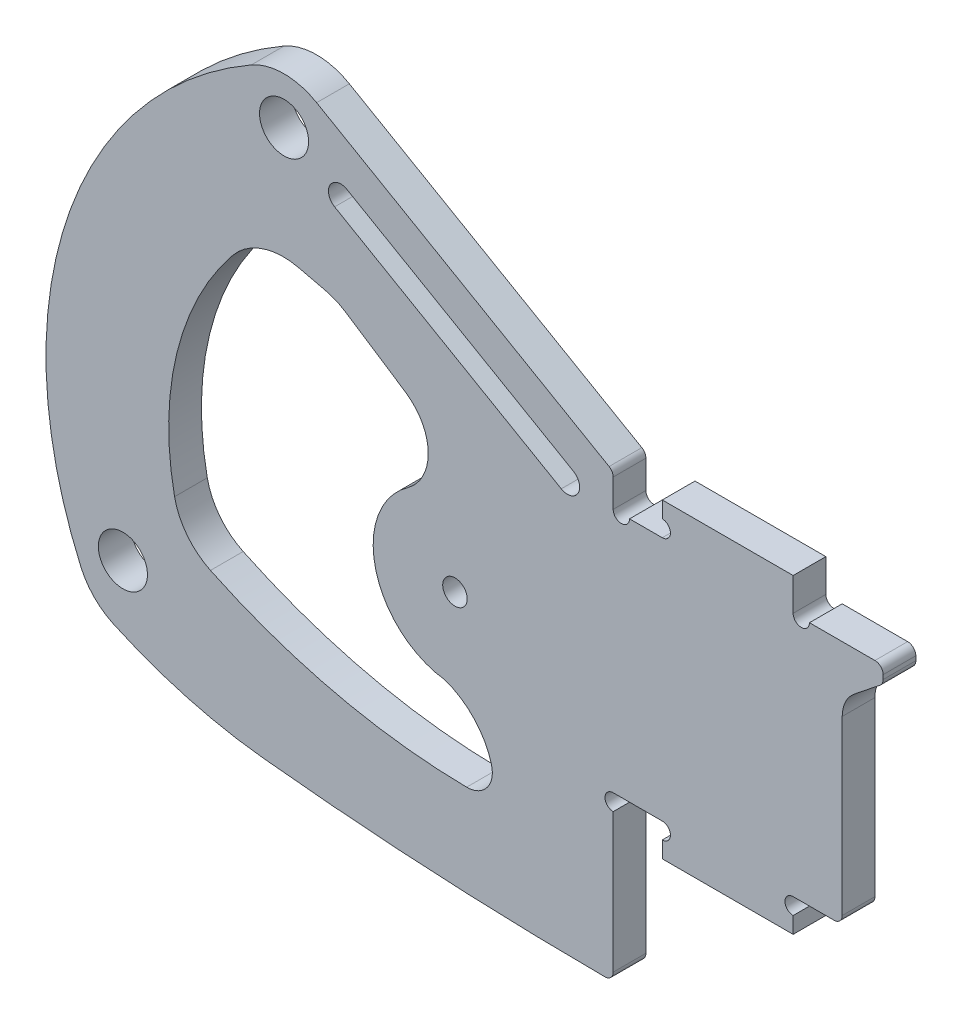
SolidWorks part; units mm, degrees
ref_plane "Front Plane" through (0, 0, 0) normal (0, 0, 1) x (1, 0, 0)
ref_plane "Top Plane" through (0, 0, 0) normal (0, 1, 0) x (1, 0, 0)
ref_plane "Right Plane" through (0, 0, 0) normal (1, 0, 0) x (0, 0, -1)
sketch "Sketch1" plane through (0, 0, 0) normal (0, 0, 1) x (1, 0, 0)
  line L0 (9.9001, 0) -> (9.9001, -2)
  line L1 (9.9001, -2) -> (1.9001, -2)
  line L2 (1.9001, -2) -> (1.9001, 0)
  line L3 (1.9001, 0) -> (-1.0999, 0)
  line L4 (9.9001, 0) -> (12.9001, 0)
  line L5 (12.9001, 0) -> (12.9001, 15)
  line L6 (12.9001, 15) -> (9.9001, 15)
  line L7 (9.9001, 15) -> (9.9001, 17)
  line L8 (9.9001, 17) -> (1.9001, 17)
  line L9 (1.9001, 17) -> (1.9001, 15)
  line L10 (1.9001, 15) -> (-1.0999, 15)
  line L11 (-1.0999, 0) -> (-1.0999, -3)
  line L12 (-1.0999, -3) -> (-17.0999, -3)
  line L13 (-1.0999, 15) -> (-1.0999, 17)
  line L14 (-1.0999, 17) -> (-21.1097, 28.5527)
  line L15 (-1.0999, -3) -> (-1.0999, -10)
  line L19 (12.9001, 15) -> (15.4001, 15)
  line L20 (15.4001, 15) -> (15.4001, 14)
  line L21 (15.4001, 14) -> (12.9001, 12)
  circle A0 centre (-10.7716, 5.7903) radius 0.75
  arc A1 (-21.1097, 28.5527) -> (-32.9795, -5.6905) centre (-10.7716, 5.7903) ccw
  arc A2 (-17.0999, -3) -> (-34.6261, -1.6905) centre (-17.0999, 114.935) cw
  arc A3 (-1.0999, -10) -> (-22.4673, -8.8664) centre (-1.0999, 191.9481) cw
  arc A4 (-22.4673, -8.8664) -> (-32.9795, -5.6905) centre (-19.3489, 20.4405) cw
  arc A5 (-15.3893, 25.25) -> (-29.0194, -2.3961) centre (-10.7716, 5.7903) ccw
  arc A6 (-1.0999, 0) -> (-1.0999, -1) centre (-1.0999, -0.5) ccw
  arc A7 (1.9001, 0) -> (1.9001, -1) centre (1.9001, -0.5) cw
  arc A8 (9.9001, 0) -> (9.9001, -1) centre (9.9001, -0.5) ccw
  arc A9 (9.9001, 15) -> (10.8983, 15) centre (10.3992, 15) ccw
  arc A10 (1.9001, 15) -> (1.9001, 16) centre (1.9001, 15.5) ccw
  arc A11 (-1.0999, 15) -> (-0.0999, 15) centre (-0.5999, 15) ccw
  dimension "D15" = 1.5
  dimension "D16" = 25
  dimension "D17" = 5
  dimension "D18" = 1
  dimension "D24" = 1
  dimension "D25" = 0.4991
  dimension "D26" = 0.5
  dimension "D27" = 0.5
  dimension "D1" = 3
  dimension "D2" = 8
  dimension "D3" = 8
  dimension "D4" = 3
  dimension "D5" = 3
  dimension "D6" = 3
  dimension "D7" = 2
  dimension "D8" = 2
  dimension "D9" = 15
  dimension "D10" = 3
  dimension "D11" = 2
  dimension "D12" = 2
  dimension "D13" = 120
  dimension "D14" = 16
  dimension "D19" = 4
  dimension "D20" = 7
  dimension "D21" = 12
  dimension "D22" = 2.5
  dimension "D23" = 1
extrude "Boss-Extrude1" add sketch "Sketch1" along normal blind 2
sketch "Sketch2" plane through (0, 0, 2) normal (0, 0, 1) x (1, 0, 0)
  line L0 (-21.2188, 25.1515) -> (-2.9644, 14.6123) construction
  line L1 (-1.0999, 17) -> (-21.1097, 28.5527) construction
  line L3 (-22.5737, 18.7117) -> (-18.0196, 17.6367)
  line L4 (-18.0196, 17.6367) -> (-12.8399, 14.2323)
  line L5 (-12.8399, 14.2323) -> (-11.4508, 10.744)
  line L6 (-17.7547, 23.1515) -> (-3.8983, 15.1515) construction
  line L7 (-17.3797, 23.8011) -> (-3.5233, 15.8011)
  line L8 (-18.1297, 22.502) -> (-4.2733, 14.502)
  circle A0 centre (-31.0713, -2.6905) radius 1.5
  circle A1 centre (-21.2188, 25.1515) radius 1.5
  arc A3 (-21.2188, 25.1515) -> (-31.0713, -2.6905) centre (-10.7716, 5.7903) ccw construction
  arc A4 (-22.5737, 18.7117) -> (-27.3919, 0.3116) centre (-10.7716, 5.7903) ccw
  circle A5 centre (-10.7716, 5.7903) radius 5
  arc A6 (-27.3919, 0.3116) -> (-10.0581, -4.1848) centre (-9.5992, 33.244) ccw
  arc A7 (-10.0581, -4.1848) -> (-8.5415, -2.2265) centre (-10.0391, -2.6331) ccw
  arc A8 (-8.5415, -2.2265) -> (-11.3871, 0.8284) centre (-12.8637, -3.3998) ccw
  arc A9 (-17.3797, 23.8011) -> (-18.1297, 22.502) centre (-17.7547, 23.1515) ccw
  arc A10 (-4.2733, 14.502) -> (-3.5233, 15.8011) centre (-3.8983, 15.1515) ccw
  point P14 (-10.8265, 19.1515)
  dimension "D1" = 3
  dimension "D2" = 3
  dimension "D7" = 17.5
  dimension "D9" = 16
  dimension "D8" = 10
  dimension "D4" = 22
  dimension "D12" = 0.75
  dimension "D5" = 3
  dimension "D6" = 3
  dimension "D11" = 3
  dimension "D13" = 4
fillet "Fillet7" radius 4 2 edges at (-21.1097, 28.5527, 1) (-32.9795, -5.6905, 1)
fillet "Fillet8" radius 0.5 5 edges at (-1.0999, -10, 1) (-1.0999, 17, 1) (15.4001, 15, 1) (15.4001, 14, 1) (12.9001, 0, 1)
fillet "Fillet9" radius 2 1 edges at (12.9001, 12, 1)
extrude "Cut-Extrude1" cut sketch "Sketch2" against normal through all contours A1 | A0 | A7 A8 A5 L5 L4 L3 A4 A6 | L8 A10 L7 A9
fillet "Fillet10" radius 4 4 edges at (-27.3919, 0.3116, 1) (-12.8399, 14.2323, 1) (-18.0196, 17.6367, 1) (-22.5737, 18.7117, 1)
fillet "Fillet12" radius 3 1 edges at (-11.4508, 10.744, 1)
